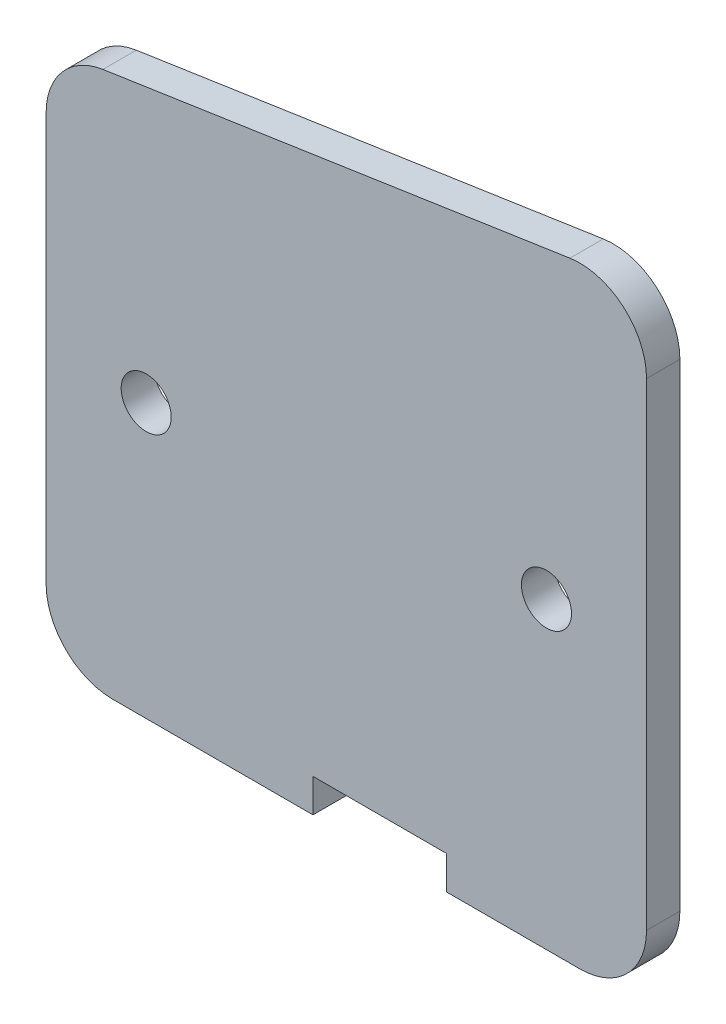
SolidWorks part; units mm, degrees
ref_plane "Front Plane" through (0, 0, 0) normal (0, 0, 1) x (1, 0, 0)
ref_plane "Top Plane" through (0, 0, 0) normal (0, 1, 0) x (1, 0, 0)
ref_plane "Right Plane" through (0, 0, 0) normal (1, 0, 0) x (0, 0, -1)
sketch "Sketch1" plane through (0, 0, 0) normal (0, 0, 1) x (1, 0, 0)
  line L0 (-60.325, 0) -> (-79.375, 0)
  line L1 (-34.925, 0) -> (-47.625, 0)
  line L4 (-38.1, 0) -> (-38.1, 57.785)
  line L5 (-76.2, 0) -> (-76.2, 52.07)
  line L13 (-28.575, 6.35) -> (-28.575, 51.8402)
  line L14 (-85.725, 6.35) -> (-85.725, 45.1727)
  line L15 (-80.317, 51.4525) -> (-35.867, 58.12)
  line L17 (-60.325, 0) -> (-60.325, 3.175)
  line L18 (-60.325, 3.175) -> (-47.625, 3.175)
  line L19 (-47.625, 0) -> (-47.625, 3.175)
  line L20 (-114.3, 0) -> (-114.3, 46.355) [skipped]
  line L21 (-152.4, 0) -> (-152.4, 40.64) [skipped]
  line L22 (-190.5, 0) -> (-190.5, 34.925) [skipped]
  line L23 (-228.6, 0) -> (-228.6, 29.21) [skipped]
  line L24 (-266.7, 0) -> (-266.7, 23.495) [skipped]
  line L25 (-304.8, 0) -> (-304.8, 17.78) [skipped]
  line L26 (-342.9, 0) -> (-342.9, 12.065) [skipped]
  circle A0 centre (-76.2, 26.035) radius 2.3813
  circle A1 centre (-38.1, 28.8925) radius 2.3812
  arc A2 (-85.725, 6.35) -> (-79.375, 0) centre (-79.375, 6.35) ccw
  arc A3 (-28.575, 6.35) -> (-34.925, 0) centre (-34.925, 6.35) cw
  arc A4 (-28.575, 51.8402) -> (-35.867, 58.12) centre (-34.925, 51.8402) ccw
  arc A5 (-85.725, 45.1727) -> (-80.317, 51.4525) centre (-79.375, 45.1727) cw
  point P4 (-85.725, 0)
  dimension "D8" = 4.7625
  dimension "D9" = 4.7625
  dimension "D2" = 6.35
  dimension "D6" = 9.525
  dimension "D7" = 9.525
  dimension "D10" = 12.7
  dimension "D11" = 3.175
  dimension "D12" = 19.05
  dimension "D5" = 9
extrude "Boss-Extrude1" add sketch "Sketch1" along normal blind 3.175 contours A5 L14 A2 L0 L5 A0 L15 | A1 L4 L15 L5 A0 L0 L17 L18 L19 L1 | L13 A4 L15 L4 A1 L1 A3
